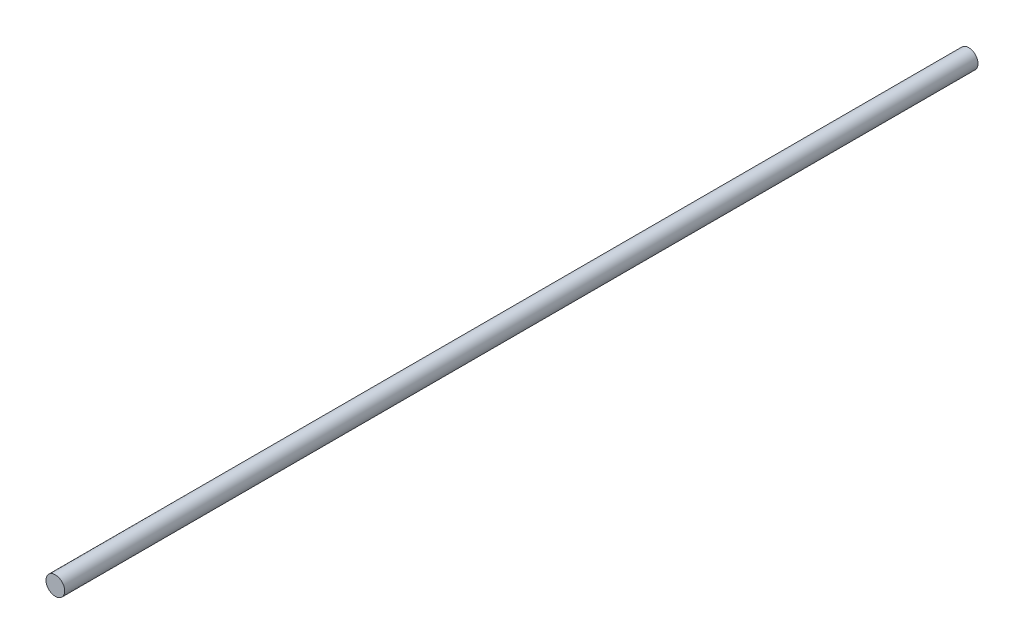
SolidWorks part; units mm, degrees
ref_plane "Front Plane" through (0, 0, 0) normal (0, 0, 1) x (1, 0, 0)
ref_plane "Top Plane" through (0, 0, 0) normal (0, 1, 0) x (1, 0, 0)
ref_plane "Right Plane" through (0, 0, 0) normal (1, 0, 0) x (0, 0, -1)
sketch "Sketch2" plane through (0, 0, 0) normal (0, 0, 1) x (1, 0, 0)
  circle A0 centre (0, 0) radius 4
  dimension "D1" = 8
extrude "Boss-Extrude1" add sketch "Sketch2" along normal mid plane 390
